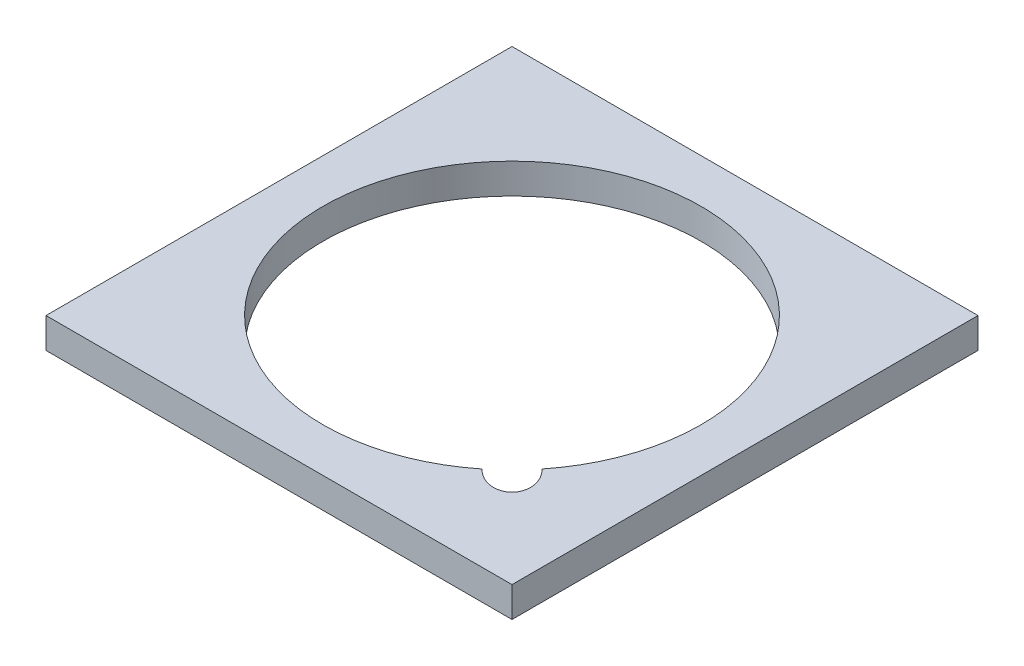
SolidWorks part; units mm, degrees
ref_plane "Front Plane" through (0, 0, 0) normal (0, 0, 1) x (1, 0, 0)
ref_plane "Top Plane" through (0, 0, 0) normal (0, 1, 0) x (1, 0, 0)
ref_plane "Right Plane" through (0, 0, 0) normal (1, 0, 0) x (0, 0, -1)
sketch "Sketch1" plane through (0, 0, 0) normal (0, 1, 0) x (1, 0, 0)
  line L0 (77, 154) -> (77, -29.0649) construction
  line L1 (0, 0) -> (154, 0)
  line L2 (0, 0) -> (0, 154)
  line L3 (0, 154) -> (154, 154)
  line L4 (154, 0) -> (154, 154)
  line L5 (0, 77) -> (194.3131, 77) construction
  line L6 (77, 77) -> (139.4977, 14.5023) construction
  line L7 (139.5, 77) -> (139.5, 115.9771) construction
  line L8 (14.5, 77) -> (14.5, 119.9558) construction
  arc A0 (125.8617, 38.0284) -> (115.9716, 28.1383) centre (77, 77) ccw
  ellipse E0 centre (121.1942, 32.8058) end of major axis (114.8302, 39.1698) minor radius 7 (115.9716, 28.1383) -> (125.8617, 38.0284) ccw
  dimension "D4" = 125
  dimension "D1" = 154
  dimension "D2" = 154
  dimension "D3" = 45
  dimension "D6" = 14
  dimension "D7" = 18
extrude "Boss-Extrude1" add sketch "Sketch1" along normal blind 10
